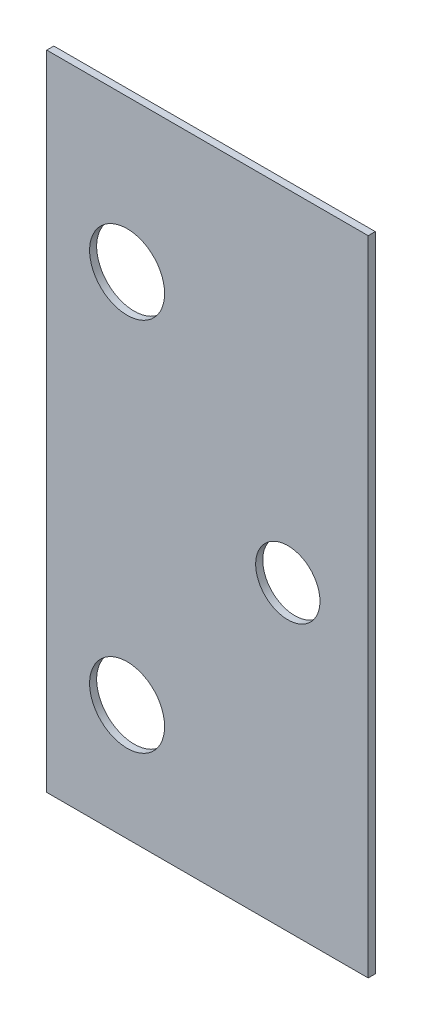
SolidWorks part; units mm, degrees
ref_plane "Front Plane" through (0, 0, 0) normal (0, 0, 1) x (1, 0, 0)
ref_plane "Top Plane" through (0, 0, 0) normal (0, 1, 0) x (1, 0, 0)
ref_plane "Right Plane" through (0, 0, 0) normal (1, 0, 0) x (0, 0, -1)
sketch "Sketch1" plane through (0, 0, 0) normal (0, 0, 1) x (1, 0, 0)
  line L1 (-22.74, -35.9637) -> (15.36, -35.9637)
  line L2 (-22.74, -35.9637) -> (-22.74, 40.2363)
  line L3 (-22.74, 40.2363) -> (15.36, 40.2363)
  line L4 (15.36, -35.9637) -> (15.36, 40.2363)
  line L5 (-22.74, -35.9637) -> (15.36, 40.2363) construction
  line L6 (-22.74, 40.2363) -> (15.36, -35.9637) construction
  point P0 (-3.69, 2.1363)
  dimension "D1" = 76.2
  dimension "D2" = 38.1
  dimension "D3" = 3.69
  dimension "D4" = 2.1363
extrude "Boss-Extrude1" add sketch "Sketch1" along normal blind 0.8382
sketch "Sketch2" plane through (0, 0, 0.8382) normal (0, 0, 1) x (1, 0, 0)
  line L0 (-22.74, 40.2363) -> (-22.74, -35.9637) construction
  line L1 (-22.74, -35.9637) -> (15.36, -35.9637) construction
  line L3 (15.36, -35.9637) -> (15.36, 40.2363) construction
  line L4 (-13.215, 22.225) -> (-13.215, -22.225) construction
  circle A0 centre (5.835, -0.1473) radius 3.81
  circle A1 centre (-13.215, 22.225) radius 4.445
  circle A2 centre (-13.215, -22.225) radius 4.445
  point P8 (0, 0)
  point P12 (7.0541, 0)
  point P17 (-13.215, 0)
  dimension "D1" = 7.62
  dimension "D7" = 8.89
  dimension "D2" = 9.525
  dimension "D3" = 35.8163
  dimension "D4" = 44.45
  dimension "D5" = 9.525
extrude "Cut-Extrude1" cut sketch "Sketch2" against normal through all
